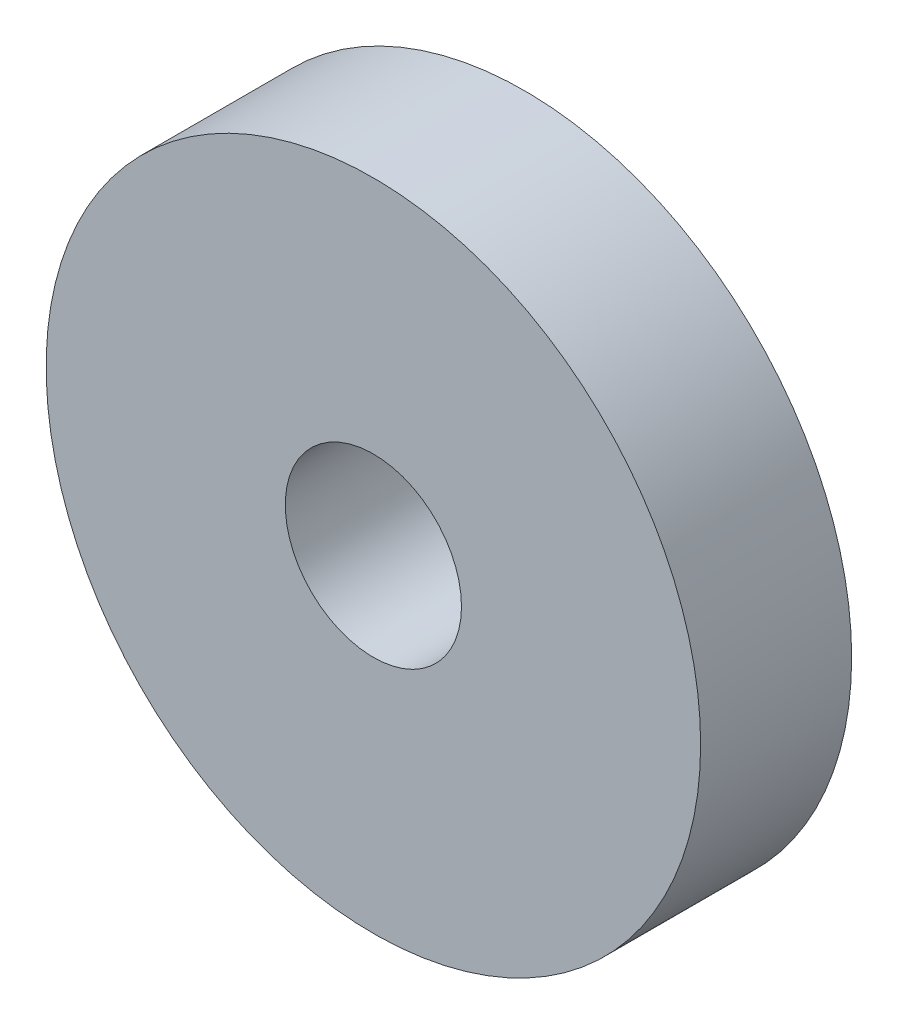
SolidWorks part; units mm, degrees
ref_plane "Front Plane" through (0, 0, 0) normal (0, 0, 1) x (1, 0, 0)
ref_plane "Top Plane" through (0, 0, 0) normal (0, 1, 0) x (1, 0, 0)
ref_plane "Right Plane" through (0, 0, 0) normal (1, 0, 0) x (0, 0, -1)
sketch "Sketch1" plane through (0, 0, 0) normal (0, 0, 1) x (1, 0, 0)
  circle A0 centre (-9.5, 0) radius 1.75
  circle A3 centre (-9.5, 0) radius 6.5
  circle A4 centre (-9.5, 0) radius 6.5
  dimension "D1" = 0.5
  dimension "D2" = 3.5
extrude "Boss-Extrude1" add sketch "Sketch1" along normal up to surface (3 mm away)
